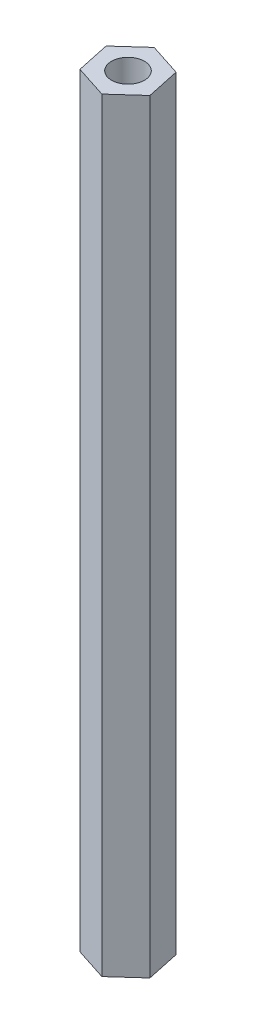
SolidWorks part; units mm, degrees
ref_plane "Plano frontal" through (0, 0, 0) normal (0, 0, 1) x (1, 0, 0)
ref_plane "Plano superior" through (0, 0, 0) normal (0, 1, 0) x (1, 0, 0)
ref_plane "Plano direito" through (0, 0, 0) normal (1, 0, 0) x (0, 0, -1)
sketch "Esboço1" plane through (0, 0, 0) normal (0, 1, 0) x (1, 0, 0)
  line L1 (3.092, -1.001) -> (2.4129, 2.1772)
  line L2 (2.4129, 2.1772) -> (-0.6791, 3.1783)
  line L3 (-0.6791, 3.1783) -> (-3.092, 1.001)
  line L4 (-3.092, 1.001) -> (-2.4129, -2.1772)
  line L5 (-2.4129, -2.1772) -> (0.6791, -3.1783)
  line L6 (0.6791, -3.1783) -> (3.092, -1.001)
  circle A0 centre (0, 0) radius 3.25 construction
extrude "Ressalto-extrusão1" add sketch "Esboço1" along normal blind 73
sketch "Esboço3" plane through (0, 0, 0) normal (0, -1, 0) x (1, 0, 0)
  point P0 (0, 0)
hole_wizard "Furo roscado para conduíte de M3x0.51" positions "Esboço6" profile "Esboço8" tap size "M3x0.5" standard "Helicoil® Metric"
sketch "Esboço6" plane through (0, 0, 0) normal (0, -1, 0) x (-1, 0, 0)
  point P0 (0, 0)
sketch "Esboço8" plane through (0, 0, 0) normal (1, 0, 0) x (0, 0, -1)
  line L0 (0, 0) -> (0, 10.9464)
  line L1 (0, 10.9464) -> (1.575, 10)
  line L2 (1.575, 10) -> (1.575, 0)
  line L5 (1.575, 0) -> (0, 0)
  line L10 (0, 10.9464) -> (-1.575, 10) construction
  line L11 (0, -6.35) -> (0, 107.95) construction
  dimension "Tap Drill Dia." = 3.15
  dimension "Tap Drill Depth" = 10
  dimension "Drill Angle" = 118
cosmetic thread "Rosca de furo1" parameters "D1"=10, "D2"=3.716
sketch "Esboço9" plane through (0, 73, 0) normal (0, 1, 0) x (1, 0, 0)
  point P0 (0, 0)
hole_wizard "Furo roscado para conduíte de M3x0.52" positions "Esboço10" profile "Esboço11" tap size "M3x0.5" standard "Helicoil® Metric"
sketch "Esboço10" plane through (0, 73, 0) normal (0, 1, 0) x (1, 0, 0)
  point P0 (0, 0)
sketch "Esboço11" plane through (0, 73, 0) normal (1, 0, 0) x (0, 0, 1)
  line L0 (0, 0) -> (0, 10.9464)
  line L1 (0, 10.9464) -> (1.575, 10)
  line L2 (1.575, 10) -> (1.575, 0)
  line L5 (1.575, 0) -> (0, 0)
  line L10 (0, 10.9464) -> (-1.575, 10) construction
  line L11 (0, -6.35) -> (0, 107.95) construction
  dimension "Tap Drill Dia." = 3.15
  dimension "Tap Drill Depth" = 10
  dimension "Drill Angle" = 118
cosmetic thread "Rosca de furo2" parameters "D1"=10, "D2"=3.716
